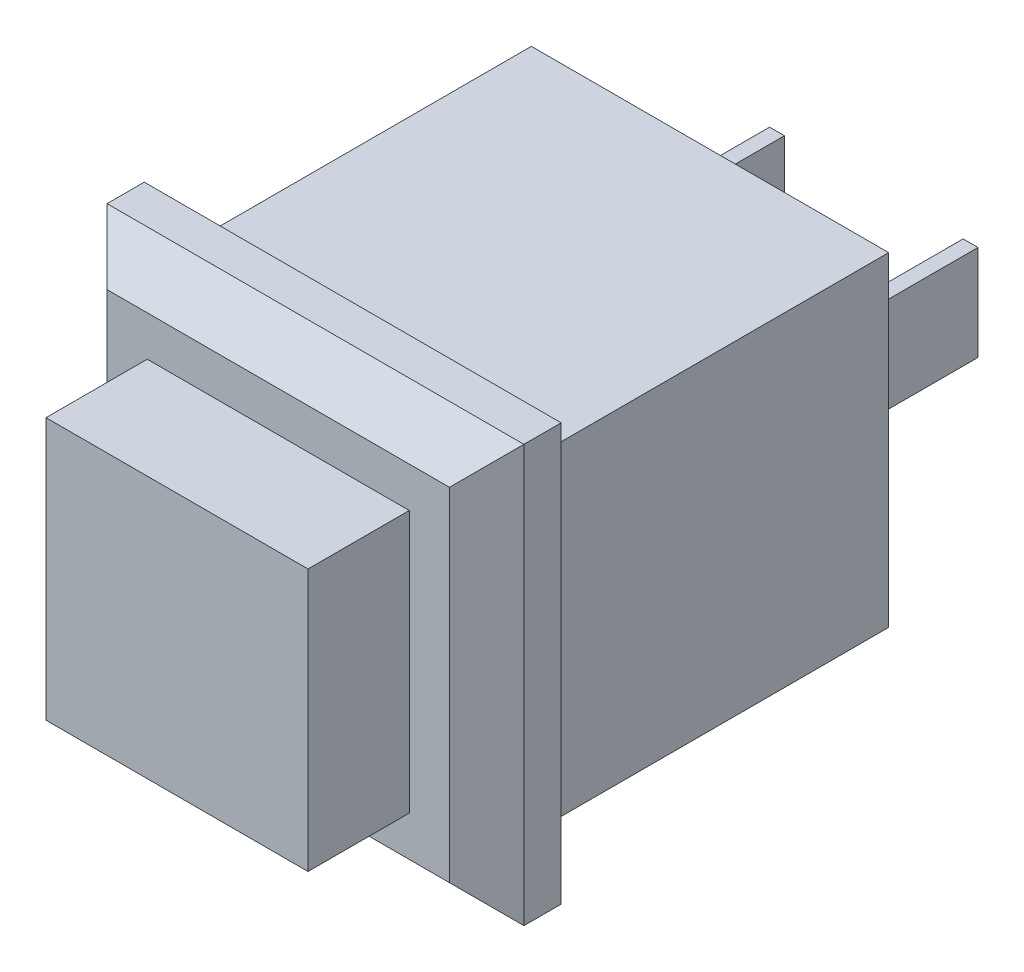
SolidWorks part; units mm, degrees
ref_plane "Front" through (0, 0, 0) normal (0, 0, 1) x (1, 0, 0)
ref_plane "Top" through (0, 0, 0) normal (0, 1, 0) x (1, 0, 0)
ref_plane "Right" through (0, 0, 0) normal (1, 0, 0) x (0, 0, -1)
sketch "Sketch1" plane through (0, 0, 0) normal (0, 0, 1) x (1, 0, 0)
  line L1 (-7, 7) -> (7, 7)
  line L2 (-7, 7) -> (-7, -7)
  line L3 (-7, -7) -> (7, -7)
  line L4 (7, 7) -> (7, -7)
  line L5 (-7, 7) -> (7, -7) construction
  line L6 (-7, -7) -> (7, 7) construction
  point P0 (0, 0)
extrude "Boss-Extrude1" add sketch "Sketch1" along normal blind 23.4
sketch "Sketch2" plane through (0, 0, 23.4) normal (0, 0, 1) x (1, 0, 0)
  line L1 (-7, 7) -> (7, 7)
  line L2 (-7, 7) -> (-7, -7)
  line L3 (-7, -7) -> (7, -7)
  line L4 (7, 7) -> (7, -7)
  line L5 (-4.4, 4.4) -> (4.4, 4.4)
  line L6 (-4.4, 4.4) -> (-4.4, -4.4)
  line L7 (-4.4, -4.4) -> (4.4, -4.4)
  line L8 (4.4, 4.4) -> (4.4, -4.4)
  line L9 (-4.4, 4.4) -> (4.4, -4.4) construction
  line L10 (-4.4, -4.4) -> (4.4, 4.4) construction
  point P4 (0, 0)
extrude "Cut-Extrude1" cut sketch "Sketch2" against normal blind 3.4
sketch "Sketch3" plane through (0, 0, 0) normal (0, 0, -1) x (-1, 0, 0)
  line L1 (-7, 7) -> (7, 7)
  line L2 (-7, 7) -> (-7, -7)
  line L3 (-7, -7) -> (7, -7)
  line L4 (7, 7) -> (7, -7)
  line L5 (-6, 5.45) -> (6, 5.45)
  line L6 (-6, 5.45) -> (-6, -5.45)
  line L7 (-6, -5.45) -> (6, -5.45)
  line L8 (6, 5.45) -> (6, -5.45)
  line L9 (-6, 5.45) -> (6, -5.45) construction
  line L10 (-6, -5.45) -> (6, 5.45) construction
  point P4 (0, 0)
extrude "Cut-Extrude2" cut sketch "Sketch3" against normal blind 17.5
sketch "Sketch4" plane through (0, 0, 0) normal (0, 0, -1) x (-1, 0, 0)
  line L0 (-6, 0) -> (6, 0) construction
  line L1 (-6, 5.45) -> (-6, -5.45) construction
  line L2 (6, -5.45) -> (6, 5.45) construction
  line L3 (0, 5.45) -> (0, -5.45) construction
  line L4 (-6, 5.45) -> (6, 5.45)
  line L5 (-6, 5.45) -> (-6, -5.45)
  line L6 (-6, -5.45) -> (6, -5.45)
  line L7 (6, 5.45) -> (6, -5.45)
  line L8 (-3.5, 1.6) -> (-3, 1.6)
  line L9 (-3.5, 1.6) -> (-3.5, -1.6)
  line L10 (-3.5, -1.6) -> (-3, -1.6)
  line L11 (-3, 1.6) -> (-3, -1.6)
  line L12 (-3.5, 1.6) -> (-3, -1.6) construction
  line L13 (-3.5, -1.6) -> (-3, 1.6) construction
  line L14 (3.5, -1.6) -> (3, 1.6) construction
  line L15 (3.5, 1.6) -> (3, -1.6) construction
  line L16 (3, 1.6) -> (3, -1.6)
  line L17 (3.5, -1.6) -> (3, -1.6)
  line L18 (3.5, 1.6) -> (3.5, -1.6)
  line L19 (3.5, 1.6) -> (3, 1.6)
  point P10 (-3.25, 0)
  point P24 (3.25, 0)
  dimension "D1" = 3.25
extrude "Cut-Extrude3" cut sketch "Sketch4" against normal blind 5.5
chamfer "Chamfer1" distance 1.25 angle 45 4 edges at (-7, 0, 20) (0, 7, 20) (7, 0, 20) (0, -7, 20)
